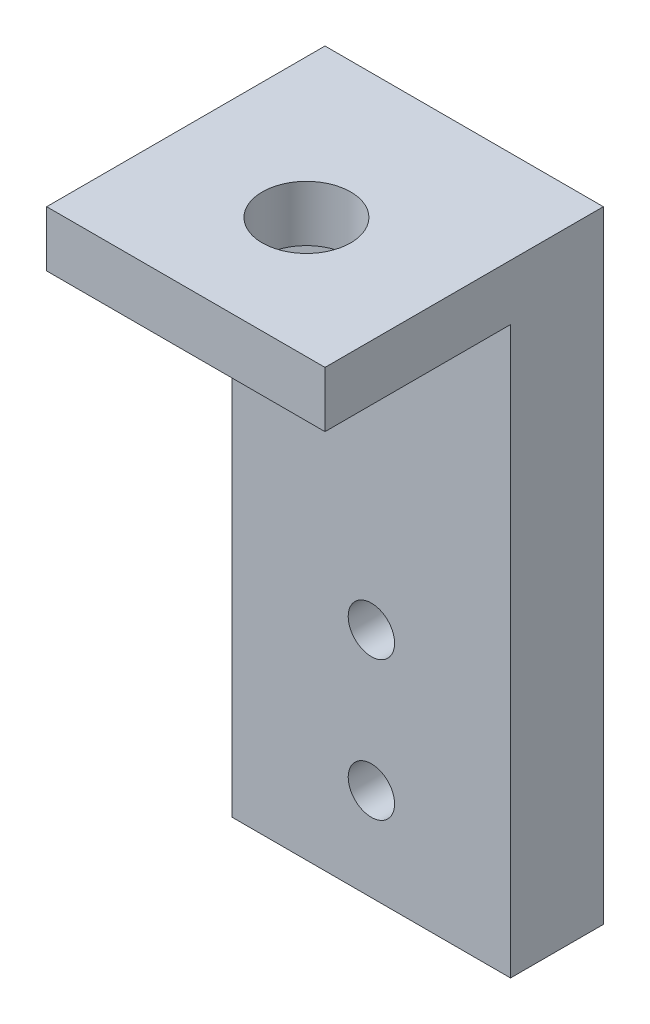
SolidWorks part; units mm, degrees
ref_plane "Plano frontal" through (0, 0, 0) normal (0, 0, 1) x (1, 0, 0)
ref_plane "Plano superior" through (0, 0, 0) normal (0, 1, 0) x (1, 0, 0)
ref_plane "Plano direito" through (0, 0, 0) normal (1, 0, 0) x (0, 0, -1)
sketch "Esboço1" plane through (0, 0, 0) normal (0, 0, 1) x (1, 0, 0)
  line L0 (15, 33.5) -> (-15, -33.5) construction
  line L1 (-15, 33.5) -> (15, 33.5)
  line L2 (-15, 33.5) -> (-15, -33.5)
  line L3 (-15, -33.5) -> (15, -33.5)
  line L4 (15, 33.5) -> (15, -33.5)
  dimension "D1" = 67
  dimension "D2" = 30
extrude "Ressalto-extrusão1" add sketch "Esboço1" along normal blind 10
sketch "Esboço2" plane through (0, 0, 10) normal (0, 0, 1) x (1, 0, 0)
  line L0 (15, -33.5) -> (15, 33.5) construction
  line L1 (-15, 33.5) -> (15, 33.5)
  line L2 (-15, 33.5) -> (-15, 27.5)
  line L3 (-15, 27.5) -> (15, 27.5)
  line L4 (15, 33.5) -> (15, 27.5)
  dimension "D1" = 6
extrude "Ressalto-extrusão2" add sketch "Esboço2" along normal blind 20
sketch "Esboço3" plane through (0, 33.5, 0) normal (0, 1, 0) x (1, 0, 0)
  line L0 (15, -17) -> (-15, -17) construction
  line L1 (15, -30) -> (15, 0) construction
  line L2 (-15, -30) -> (-15, 0) construction
  line L3 (15, -30) -> (-15, -30) construction
  circle A0 centre (0, -17) radius 4.765
  dimension "D2" = 9.53
  dimension "D1" = 13
extrude "Corte-extrusão1" cut sketch "Esboço3" against normal up to next
sketch "Esboço4" plane through (0, 0, 0) normal (0, 0, -1) x (-1, 0, 0)
  line L0 (0, 33.5) -> (0, -33.5) construction
  line L1 (-15, 33.5) -> (15, 33.5) construction
  line L2 (15, -33.5) -> (-15, -33.5) construction
  circle A0 centre (0, -23.5) radius 2.5
  circle A1 centre (0, -8.5) radius 2.5
  dimension "D1" = 5
  dimension "D3" = 5
  dimension "D2" = 10
  dimension "D4" = 15
extrude "Corte-extrusão2" cut sketch "Esboço4" against normal blind 10
